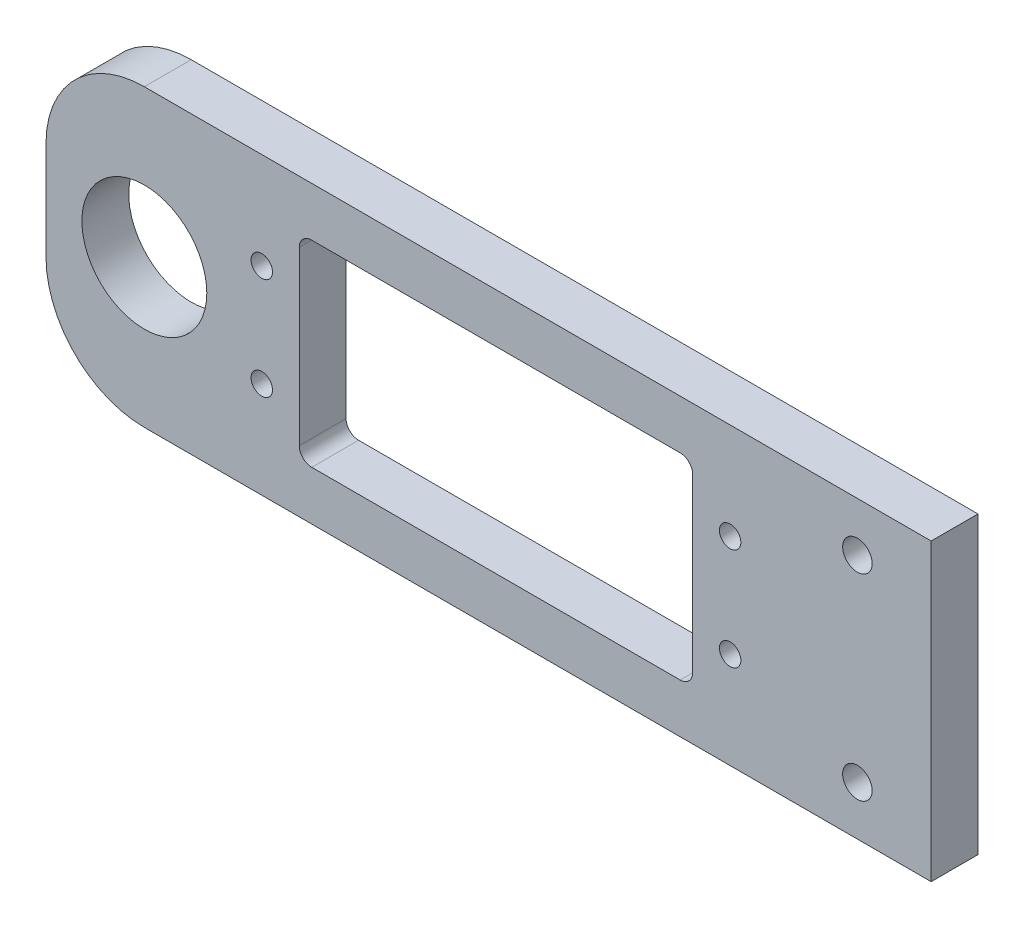
SolidWorks part; units mm, degrees
ref_plane "Front" through (0, 0, 0) normal (0, 0, 1) x (1, 0, 0)
ref_plane "Top" through (0, 0, 0) normal (0, 1, 0) x (1, 0, 0)
ref_plane "Right" through (0, 0, 0) normal (1, 0, 0) x (0, 0, -1)
sketch "Esquisse1" plane through (0, 0, 0) normal (0, 0, 1) x (1, 0, 0)
  line L1 (-45, 15) -> (45, 15)
  line L2 (-45, 15) -> (-45, -15)
  line L3 (-45, -15) -> (45, -15)
  line L4 (45, 15) -> (45, -15)
  line L5 (-45, 15) -> (45, -15) construction
  line L6 (-45, -15) -> (45, 15) construction
  point P0 (0, 0)
  dimension "D1" = 90
  dimension "D2" = 30
extrude "Boss.-Extru.1" add sketch "Esquisse1" along normal blind 4.7625
fillet "Congé1" radius 10 2 edges at (-45, -15, 2.3813) (-45, 15, 2.3813)
sketch "Esquisse2" plane through (0, 0, 4.7625) normal (0, 0, 1) x (1, 0, 0)
  line L0 (-45, 5) -> (-45, -5) construction
  line L1 (45, 15) -> (-35, 15) construction
  circle A0 centre (-35, 0) radius 6.35
  dimension "D1" = 10
  dimension "D2" = 12.7
  dimension "D3" = 15
extrude "Enlèv. mat.-Extru.1" cut sketch "Esquisse2" against normal blind 6
sketch "Esquisse5" plane through (0, 0, 4.7625) normal (0, 0, 1) x (1, 0, 0)
  line L2 (45, 15) -> (-35, 15) construction
  circle A0 centre (-9.6, 0) radius 3.5835 construction
  circle A1 centre (-35, 0) radius 6.35 construction
  dimension "D1" = 25.4
  dimension "D2" = 7.1671
  dimension "D3" = 15
sketch "Esquisse3" plane through (0, 0, 4.7625) normal (0, 0, 1) x (1, 0, 0)
  line L0 (45, 15) -> (-35, 15) construction
  line L1 (-19.25, 10) -> (20.75, 10)
  line L2 (-19.25, 10) -> (-19.25, -10)
  line L3 (-19.25, -10) -> (20.75, -10)
  line L4 (20.75, 10) -> (20.75, -10)
  circle A0 centre (-9.6, 0) radius 3.5835 construction
  dimension "D1" = 20
  dimension "D2" = 5
  dimension "D3" = 40
  dimension "D4" = 9.65
extrude "Enlèv. mat.-Extru.2" cut sketch "Esquisse3" against normal up to next
fillet "Congé2" radius 1.27 4 edges at (20.75, -10, 2.3813) (-19.25, -10, 2.3813) (20.75, 10, 2.3813) (-19.25, 10, 2.3813)
sketch "Esquisse4" plane through (0, 0, 4.7625) normal (0, 0, 1) x (1, 0, 0)
  line L0 (-19.25, 8.73) -> (-19.25, -8.73) construction
  line L1 (19.48, 10) -> (-17.98, 10) construction
  line L2 (50, 0) -> (-50, 0) construction
  line L4 (0.75, 10) -> (0.75, -10) construction
  line L5 (-17.98, -10) -> (19.48, -10) construction
  circle A0 centre (-23.06, 5.19) radius 1.09
  circle A1 centre (-23.06, -5.19) radius 1.09
  circle A2 centre (24.56, -5.19) radius 1.09
  circle A3 centre (24.56, 5.19) radius 1.09
  dimension "D3" = 2.18
  dimension "D1" = 3.81
  dimension "D2" = 4.81
extrude "Enlèv. mat.-Extru.3" cut sketch "Esquisse4" against normal up to next
sketch "Esquisse6" plane through (0, 0, 4.7625) normal (0, 0, 1) x (1, 0, 0)
  line L0 (45, -15) -> (45, 15) construction
  line L1 (45, 15) -> (-35, 15) construction
  line L2 (50, 0) -> (-50, 0) construction
  circle A0 centre (37.5, 10) radius 1.5
  circle A1 centre (37.5, -10) radius 1.5
  dimension "D1" = 3
  dimension "D2" = 7.5
  dimension "D3" = 5
extrude "Enlèv. mat.-Extru.4" cut sketch "Esquisse6" against normal up to next
